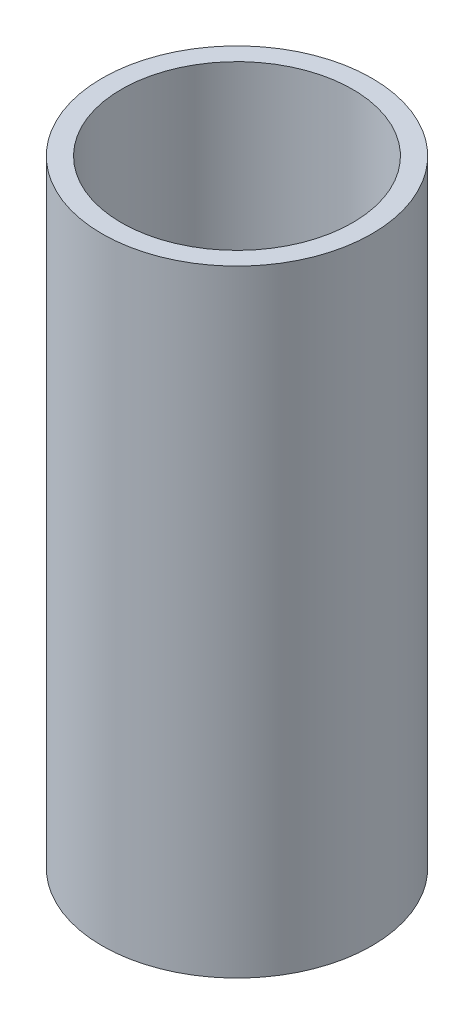
SolidWorks part; units mm, degrees
material "PVC Rigid"
ref_plane "Front Plane" through (0, 0, 0) normal (0, 0, 1) x (1, 0, 0)
ref_plane "Top Plane" through (0, 0, 0) normal (0, 1, 0) x (1, 0, 0)
ref_plane "Right Plane" through (0, 0, 0) normal (1, 0, 0) x (0, 0, -1)
sketch "Sketch1" plane through (0, 0, 0) normal (0, 1, 0) x (1, 0, 0)
  circle A0 centre (0, 0) radius 38.1
  circle A1 centre (0, 0) radius 44.45
  dimension "D1" = 76.2
  dimension "D2" = 88.9
extrude "Boss-Extrude1" add sketch "Sketch1" along normal blind 203.2
